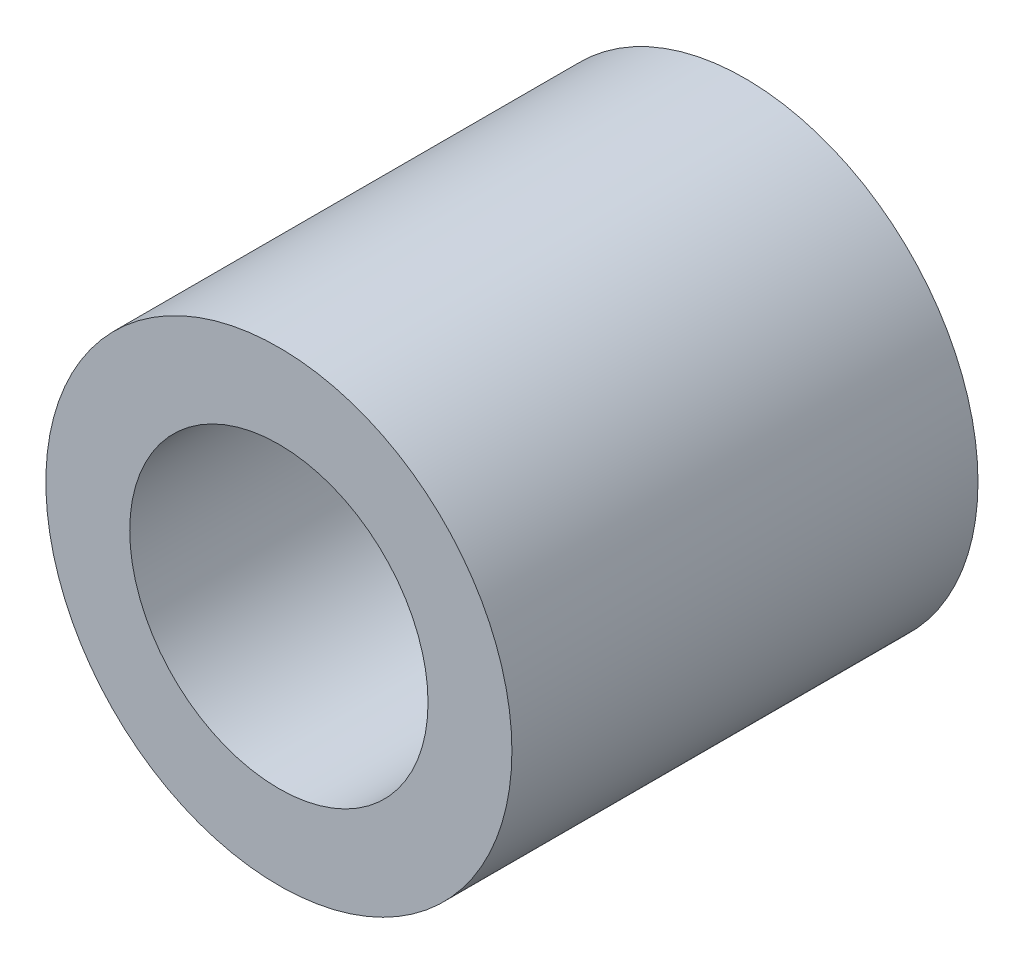
SolidWorks part; units mm, degrees
material "ABS"
ref_plane "前视基准面" through (0, 0, 0) normal (0, 0, 1) x (1, 0, 0)
ref_plane "上视基准面" through (0, 0, 0) normal (0, 1, 0) x (1, 0, 0)
ref_plane "右视基准面" through (0, 0, 0) normal (1, 0, 0) x (0, 0, -1)
other "Configuration Table"
sketch "草图1" plane through (0, 0, 0) normal (0, 0, 1) x (1, 0, 0)
  circle A0 centre (0, 0) radius 2.5
  circle A1 centre (0, 0) radius 1.6
  dimension "D1" = 5
  dimension "D2" = 3.2
extrude "凸台-拉伸1" add sketch "草图1" along normal blind 5
